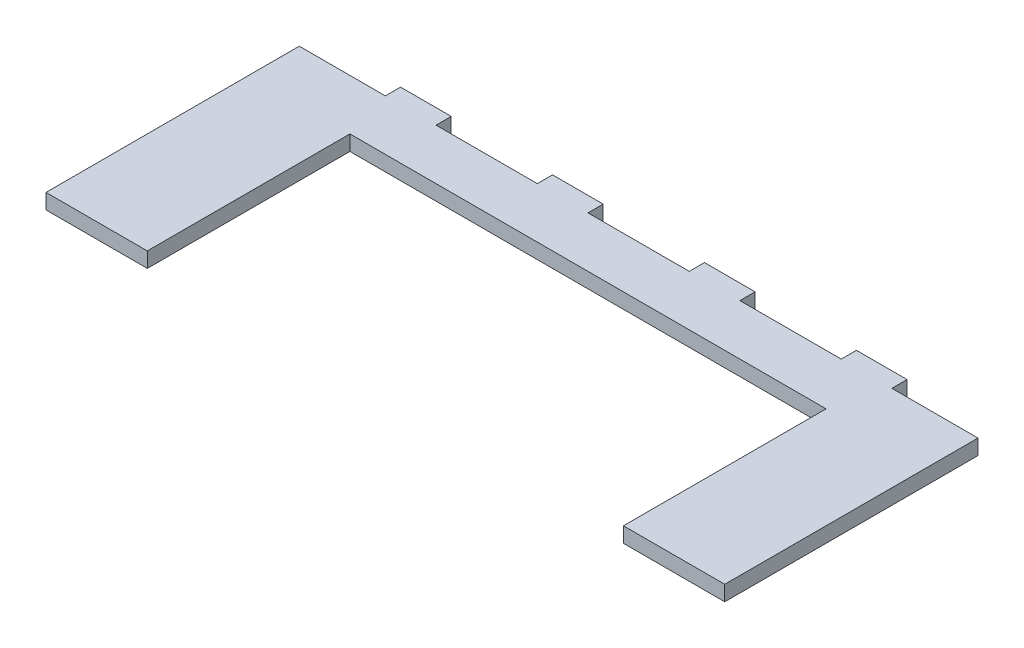
SolidWorks part; units mm, degrees
ref_plane "Front Plane" through (0, 0, 0) normal (0, 0, 1) x (1, 0, 0)
ref_plane "Top Plane" through (0, 0, 0) normal (0, 1, 0) x (1, 0, 0)
ref_plane "Right Plane" through (0, 0, 0) normal (1, 0, 0) x (0, 0, -1)
sketch "Sketch1" plane through (0, 0, 0) normal (0, 1, 0) x (1, 0, 0)
  line L1 (-67, 25) -> (67, 25)
  line L2 (-67, 25) -> (-67, -25)
  line L3 (-67, -25) -> (67, -25)
  line L4 (67, 25) -> (67, -25)
  line L5 (-67, 25) -> (67, -25) construction
  line L6 (-67, -25) -> (67, 25) construction
  point P0 (0, 0)
  dimension "D1" = 50
  dimension "D2" = 134
extrude "Boss-Extrude1" add sketch "Sketch1" along normal blind 3
sketch "Sketch2" plane through (0, 3, 0) normal (0, 1, 0) x (1, 0, 0)
  line L0 (-67, -25) -> (67, -25) construction
  line L1 (-47, -25) -> (47, -25)
  line L2 (-47, -25) -> (-47, 15)
  line L3 (-47, 15) -> (47, 15)
  line L4 (47, -25) -> (47, 15)
  line L5 (-67, 25) -> (-67, -25) construction
  line L6 (67, -25) -> (67, 25) construction
  line L7 (67, 25) -> (-67, 25) construction
  dimension "D1" = 20
  dimension "D2" = 20
  dimension "D3" = 10
extrude "Cut-Extrude1" cut sketch "Sketch2" against normal blind 13
sketch "Sketch3" plane through (0, 0, -25) normal (0, 0, -1) x (-1, 0, 0)
  line L0 (-67, 0) -> (67, 0) construction
  line L1 (-50, 0) -> (-40, 0)
  line L2 (-50, 0) -> (-50, 3)
  line L3 (-50, 3) -> (-40, 3)
  line L4 (-40, 0) -> (-40, 3)
  line L5 (-67, 3) -> (67, 3) construction
  line L6 (-67, 3) -> (-67, 0) construction
  line L7 (-20, 0) -> (-20, 3)
  line L8 (-20, 0) -> (-10, 0)
  line L9 (-10, 0) -> (-10, 3)
  line L10 (-20, 3) -> (-10, 3)
  line L11 (10, 0) -> (10, 3)
  line L12 (10, 0) -> (20, 0)
  line L13 (20, 0) -> (20, 3)
  line L14 (10, 3) -> (20, 3)
  line L15 (40, 0) -> (40, 3)
  line L16 (40, 0) -> (50, 0)
  line L17 (50, 0) -> (50, 3)
  line L18 (40, 3) -> (50, 3)
  dimension "D1" = 17
  dimension "D2" = 10
  dimension "D3" = 4
extrude "Boss-Extrude2" add sketch "Sketch3" along normal blind 3
